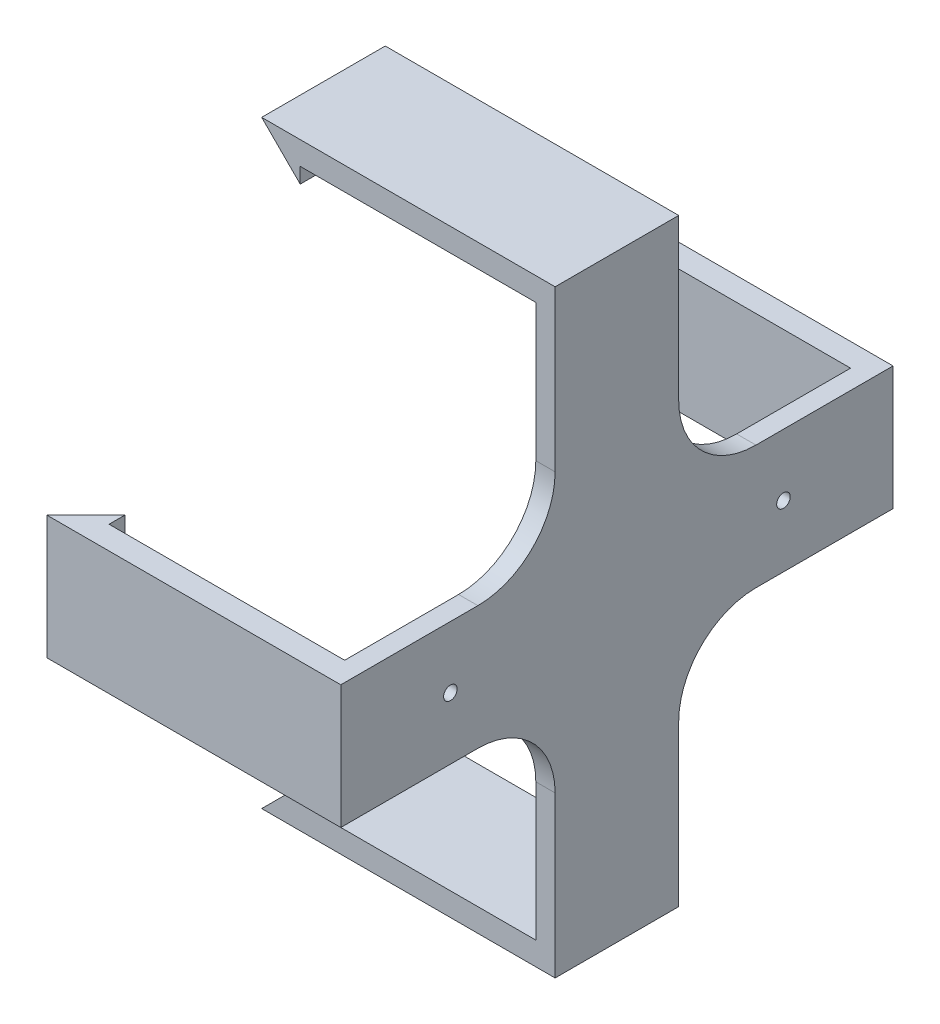
SolidWorks part; units mm, degrees
ref_plane "Front Plane" through (0, 0, 0) normal (0, 0, 1) x (1, 0, 0)
ref_plane "Top Plane" through (0, 0, 0) normal (0, 1, 0) x (1, 0, 0)
ref_plane "Right Plane" through (0, 0, 0) normal (1, 0, 0) x (0, 0, -1)
sketch "Sketch2" plane through (0, 0, 0) normal (1, 0, 0) x (0, 0, -1)
  line L0 (-208.9481, 0) -> (207.6242, 0) construction
  line L1 (0, 125.0642) -> (0, -152.4123) construction
  line L2 (-20.32, 90.805) -> (20.32, 90.805)
  line L3 (20.32, 90.805) -> (20.32, 45.72)
  line L4 (45.72, 20.32) -> (83.185, 20.32)
  line L5 (83.185, 20.32) -> (83.185, -20.32)
  line L6 (83.185, 0) -> (-83.185, 0)
  line L7 (0, -90.805) -> (0, 90.805)
  line L8 (83.185, -20.32) -> (90.805, -20.32)
  line L9 (20.32, 90.805) -> (-20.32, 90.805)
  line L10 (20.32, 90.805) -> (20.32, 98.425)
  line L11 (20.32, 98.425) -> (-20.32, 98.425)
  line L12 (0, 90.805) -> (0, 98.425)
  line L13 (83.185, 20.32) -> (90.805, 20.32)
  line L14 (83.185, 20.32) -> (83.185, -20.32)
  line L15 (83.185, 0) -> (90.805, 0)
  line L16 (90.805, 20.32) -> (90.805, -20.32)
  line L17 (0, -90.805) -> (0, -98.425)
  line L18 (20.32, -98.425) -> (-20.32, -98.425)
  line L19 (20.32, -90.805) -> (20.32, -98.425)
  line L20 (20.32, -90.805) -> (-20.32, -90.805)
  line L21 (45.72, -20.32) -> (83.185, -20.32)
  line L22 (20.32, -90.805) -> (20.32, -45.72)
  line L23 (-20.32, -90.805) -> (20.32, -90.805)
  line L24 (208.9481, 0) -> (-207.6242, 0) construction
  line L25 (-20.32, -90.805) -> (-20.32, -45.72)
  line L26 (-45.72, -20.32) -> (-83.185, -20.32)
  line L27 (-20.32, -90.805) -> (-20.32, -98.425)
  line L28 (-90.805, 20.32) -> (-90.805, -20.32)
  line L29 (-83.185, 0) -> (-90.805, 0)
  line L30 (-83.185, 20.32) -> (-83.185, -20.32)
  line L31 (-83.185, 20.32) -> (-90.805, 20.32)
  line L32 (-20.32, 90.805) -> (-20.32, 98.425)
  line L33 (-83.185, -20.32) -> (-90.805, -20.32)
  line L34 (-83.185, 20.32) -> (-83.185, -20.32)
  line L35 (-45.72, 20.32) -> (-83.185, 20.32)
  line L36 (-20.32, 90.805) -> (-20.32, 45.72)
  arc A0 (45.72, 20.32) -> (20.32, 45.72) centre (45.72, 45.72) cw
  arc A1 (45.72, -20.32) -> (20.32, -45.72) centre (45.72, -45.72) ccw
  arc A2 (-45.72, -20.32) -> (-20.32, -45.72) centre (-45.72, -45.72) cw
  arc A3 (-45.72, 20.32) -> (-20.32, 45.72) centre (-45.72, 45.72) ccw
  circle A4 centre (54.7651, 0) radius 2.2225
  circle A5 centre (-54.7651, 0) radius 2.2225
  point P44 (0, 0)
  dimension "D1" = 25.4
  dimension "D8" = 4.445
  dimension "D2" = 20.32
  dimension "D3" = 20.32
  dimension "D4" = 83.185
  dimension "D5" = 90.805
  dimension "D6" = 7.62
  dimension "D7" = 7.62
extrude "Boss-Extrude1" add sketch "Sketch2" along normal blind 6.35 contours L4 A0 L3 L2 L7 L6 L5 | A3 L35 L30 L6 L7 L2 L36 | L32 L2 L12 L11 | L12 L2 L10 L11 | L16 L13 L5 L15 | L16 L15 L5 L8 | A1 L21 L5 L6 L7 L20 L22 | L26 A2 L25 L20 L7 L6 L30 | L33 L30 L29 L28 | L30 L31 L28 L29 | L20 L27 L18 L17 | L19 L20 L17 L18
sketch "Sketch3" plane through (0, 0, 0) normal (-1, 0, 0) x (0, 0, 1)
  line L1 (-20.32, 98.425) -> (20.32, 98.425)
  line L2 (-20.32, 98.425) -> (-20.32, 90.805)
  line L3 (-20.32, 90.805) -> (20.32, 90.805)
  line L4 (20.32, 98.425) -> (20.32, 90.805)
  line L5 (-90.805, 20.32) -> (-83.185, 20.32)
  line L6 (-90.805, 20.32) -> (-90.805, -20.32)
  line L7 (-90.805, -20.32) -> (-83.185, -20.32)
  line L8 (-83.185, 20.32) -> (-83.185, -20.32)
  line L9 (90.805, 20.32) -> (83.185, 20.32)
  line L10 (90.805, 20.32) -> (90.805, -20.32)
  line L11 (90.805, -20.32) -> (83.185, -20.32)
  line L12 (90.805, -20.32) -> (90.805, 20.32)
  line L13 (90.805, 20.32) -> (45.72, 20.32)
  line L14 (20.32, 45.72) -> (20.32, 98.425)
  line L15 (20.32, 98.425) -> (-20.32, 98.425)
  line L16 (-20.32, 98.425) -> (-20.32, 45.72)
  line L17 (-45.72, 20.32) -> (-90.805, 20.32)
  line L18 (-90.805, 20.32) -> (-90.805, -20.32)
  line L19 (-90.805, -20.32) -> (-45.72, -20.32)
  line L20 (-20.32, -45.72) -> (-20.32, -98.425)
  line L21 (-20.32, -98.425) -> (20.32, -98.425)
  line L22 (20.32, -98.425) -> (20.32, -45.72)
  line L23 (45.72, -20.32) -> (90.805, -20.32)
  line L24 (90.805, -20.32) -> (90.805, 20.32)
  line L25 (90.805, 20.32) -> (45.72, 20.32)
  line L26 (20.32, 45.72) -> (20.32, 98.425)
  line L27 (20.32, 98.425) -> (-20.32, 98.425)
  line L28 (-20.32, 98.425) -> (-20.32, 45.72)
  line L29 (-45.72, 20.32) -> (-90.805, 20.32)
  line L30 (-90.805, 20.32) -> (-90.805, -20.32)
  line L31 (-90.805, -20.32) -> (-45.72, -20.32)
  line L32 (-20.32, -45.72) -> (-20.32, -98.425)
  line L33 (-20.32, -98.425) -> (20.32, -98.425)
  line L34 (20.32, -98.425) -> (20.32, -45.72)
  line L35 (45.72, -20.32) -> (90.805, -20.32)
  line L36 (83.185, 20.32) -> (83.185, -20.32)
  line L37 (20.32, -98.425) -> (-20.32, -98.425)
  line L38 (20.32, -98.425) -> (20.32, -90.805)
  line L39 (20.32, -90.805) -> (-20.32, -90.805)
  line L40 (-20.32, -98.425) -> (-20.32, -90.805)
  arc A4 (20.32, 45.72) -> (45.72, 20.32) centre (45.72, 45.72) ccw
  arc A5 (-45.72, 20.32) -> (-20.32, 45.72) centre (-45.72, 45.72) ccw
  arc A6 (-20.32, -45.72) -> (-45.72, -20.32) centre (-45.72, -45.72) ccw
  arc A7 (45.72, -20.32) -> (20.32, -45.72) centre (45.72, -45.72) ccw
  arc A8 (20.32, 45.72) -> (45.72, 20.32) centre (45.72, 45.72) ccw
  arc A9 (-45.72, 20.32) -> (-20.32, 45.72) centre (-45.72, 45.72) ccw
  arc A10 (-20.32, -45.72) -> (-45.72, -20.32) centre (-45.72, -45.72) ccw
  arc A11 (45.72, -20.32) -> (20.32, -45.72) centre (45.72, -45.72) ccw
  line M21 (90.805, -20.32) -> (90.805, 20.32)
  line M22 (90.805, 20.32) -> (45.72, 20.32)
  line M24 (20.32, 45.72) -> (20.32, 98.425)
  line M25 (20.32, 98.425) -> (-20.32, 98.425)
  line M26 (-20.32, 98.425) -> (-20.32, 45.72)
  line M28 (-45.72, 20.32) -> (-90.805, 20.32)
  line M29 (-90.805, 20.32) -> (-90.805, -20.32)
  line M30 (-90.805, -20.32) -> (-45.72, -20.32)
  line M33 (-20.32, -98.425) -> (20.32, -98.425)
  line M34 (20.32, -98.425) -> (20.32, -45.72)
  line M36 (45.72, -20.32) -> (90.805, -20.32)
  dimension "D1" = 0
extrude "Boss-Extrude2" add sketch "Sketch3" along normal blind 77.47 contours L8 M28 M29 M30 | L3 M26 M24 M25 | L36 M22 M36 M21 | L39 L32 M34 M33
sketch "Sketch6" plane through (0, -20.32, 0) normal (0, -1, 0) x (-1, 0, 0)
  line L0 (77.47, 90.805) -> (90.2733, 90.805)
  line L1 (90.2733, 90.805) -> (77.47, 78.0017)
  line L2 (77.47, 78.0017) -> (77.47, 90.805)
  line L3 (-82.9505, 0) -> (139.8229, 0) construction
  line L4 (90.2733, -90.805) -> (77.47, -78.0017)
  line L5 (77.47, -90.805) -> (90.2733, -90.805)
  line L6 (77.47, -78.0017) -> (77.47, -90.805)
extrude "Boss-Extrude5" add sketch "Sketch6" against normal blind 40.64
sketch "Sketch7" plane through (0, 0, -20.32) normal (0, 0, -1) x (-1, 0, 0)
  line L0 (77.47, -98.425) -> (90.1483, -98.425)
  line L1 (90.1483, -98.425) -> (77.47, -85.7467)
  line L2 (77.47, -85.7467) -> (77.47, -98.425)
  line L3 (127.6186, 0) -> (-124.2137, 0) construction
  line L4 (90.1483, 98.425) -> (77.47, 85.7467)
  line L5 (77.47, 98.425) -> (90.1483, 98.425)
  line L6 (77.47, 85.7467) -> (77.47, 98.425)
extrude "Boss-Extrude6" add sketch "Sketch7" against normal blind 40.64 contours L4 L6 L5 | L2 L0 L1
sketch "Sketch8" plane through (0, 0, 0) normal (-1, 0, 0) x (0, 0, 1)
  line L0 (0, 117.1976) -> (0, -121.0171) construction
  line L1 (0, 125.0642) -> (0, -152.4123) construction
  circle A0 centre (54.7651, 0) radius 3.937
  circle A1 centre (-54.7651, 0) radius 3.937
extrude "Cut-Extrude1" cut sketch "Sketch8" against normal blind 2.54
sketch "Sketch9" plane through (0, 0, 20.32) normal (0, 0, 1) x (1, 0, 0)
  line L0 (24.7491, 0) -> (-132.9593, 0) construction
  line L2 (0, -90.805) -> (0, -93.345)
sketch "Sketch10" plane through (0, 0, -90.805) normal (0, 0, -1) x (-1, 0, 0)
  line L4 (-6.35, -20.32) -> (90.2733, -20.32)
  line L5 (90.2733, -20.32) -> (90.2733, 20.32)
  line L6 (90.2733, 20.32) -> (-6.35, 20.32)
  line L7 (-6.35, 20.32) -> (-6.35, -20.32)
  line L8 (-6.35, -20.32) -> (90.2733, -20.32)
  line L9 (90.2733, -20.32) -> (90.2733, 20.32)
  line L10 (90.2733, 20.32) -> (-6.35, 20.32)
  line L11 (-6.35, 20.32) -> (-6.35, -20.32)
  dimension "D1" = 0
equation "\"A\"=3.05"
